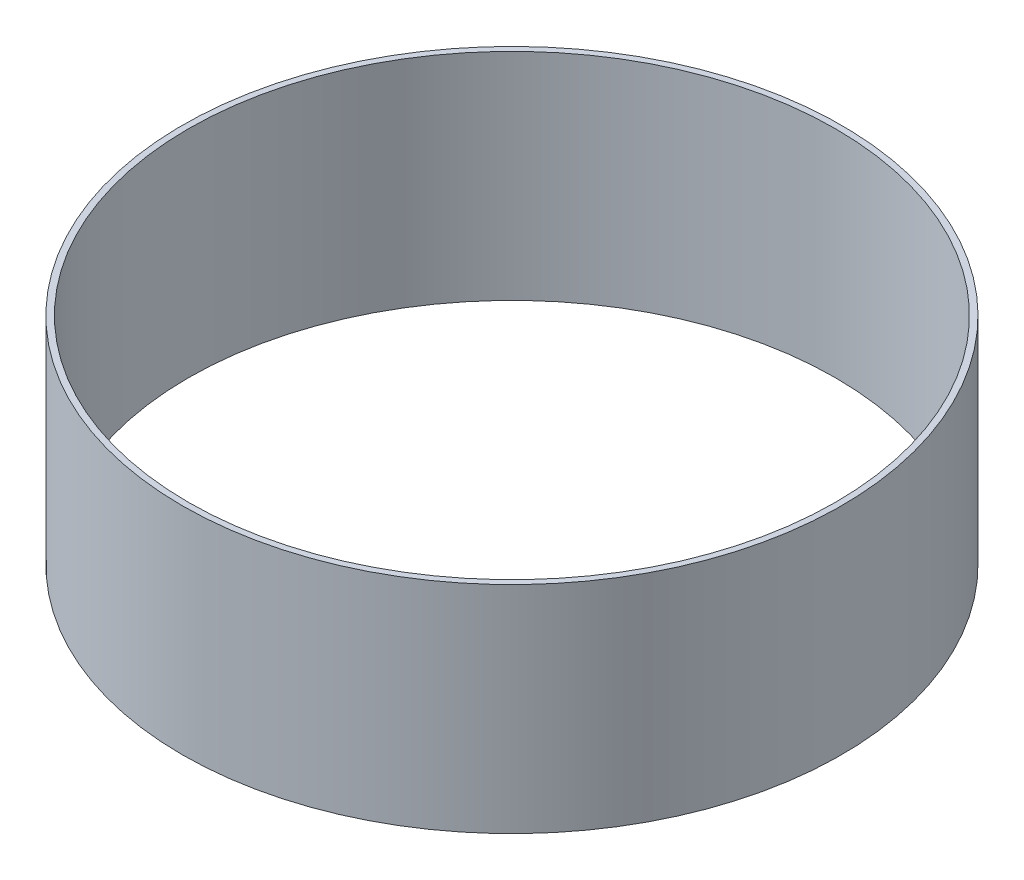
SolidWorks part; units mm, degrees
material "Thornel Mat VMA"
ref_plane "Front Plane" through (0, 0, 0) normal (0, 0, 1) x (1, 0, 0)
ref_plane "Top Plane" through (0, 0, 0) normal (0, 1, 0) x (1, 0, 0)
ref_plane "Right Plane" through (0, 0, 0) normal (1, 0, 0) x (0, 0, -1)
sketch "Sketch1" plane through (0, 0, 0) normal (0, 1, 0) x (1, 0, 0)
  circle A0 centre (0, 0) radius 76.2
  circle A1 centre (0, 0) radius 77.6224
  dimension "D1" = 152.4
  dimension "D2" = 155.2448
extrude "Boss-Extrude1" add sketch "Sketch1" along normal mid plane 50.8
extrude "Cut-Extrude1" [suppressed] cut sketch "Sketch2" against normal blind 5.08
sketch "Sketch2" plane through (54.8873, 0, -54.8873) normal (0.7071, 0, -0.7071) x (0, -1, 0)
  circle A0 centre (0, 0) radius 6.35
pattern_circular "CirPattern1" [suppressed] count 4 over 360
equation "\"airframeInnerDiameter\"= 6in"
equation "\"outerDiameter\"= 6.112in"
equation "\"airframeBulkheadThickness\"= 0.125in"
equation "\"payloadAirframeLength\"= 10in"
equation "\"payloadInnerDiameter\"= 6in - 0.056in"
equation "\"payloadOuterDiameter\"= \"airframeInnerDiameter\""
equation "\"payloadLength\"= 11in"
equation "\"payloadBand\"= 2in"
equation "\"payloadOffsetFromAft\"= 6in"
equation "\"upperAirframeLength\"= 25in"
equation "\"recoveryBayInnerDiameter\"= 5.888in"
equation "\"recoveryLength\"= 8in"
equation "\"recoveryBand\"= 2in"
equation "\"recoveryCouplerOuter\"=\"airframeInnerDiameter\""
equation "\"recoveryOffsetFromAft\"= 3in"
equation "\"midAirframeLength\"= 20in"
equation "\"atsLength\"= 11in"
equation "\"atsInner\"= 5.888in"
equation "\"atsBand\"= 2in"
equation "\"atsCouplerOuter\"=\"airframeInnerDiameter\""
equation "\"atsOffsetFromAft\"= 3in"
equation "\"lowerAirframeLength\"= 40in"
equation "\"motorTubeOuterDiameter\"= 4.25in"
equation "\"motorTubeInnerDiameter\"= 4in"
equation "\"motorTubeLength\"= 32in"
equation "\"centeringRingOuterDiameter\"= \"airframeInnerDiameter\""
equation "\"centeringRingInnerDiameter\"= \"motorTubeOuterDiameter\""
equation "\"centeringRingThickness\"= 0.375in"
equation "\"topCenteringRingOffsetFromAft\"= 16.7in"
equation "\"bottomCenteringRingOffsetFromAft\"= 0.3in"
equation "\"finSlotLength\"= 8in"
equation "\"finSlotOffsetFromAft\"= 3in"
equation "\"finSlotWidth\"= 0.187in"
equation "\"motorCasingOuterDiameter\"= 3in"
equation "\"motorCasingCenteringRingThickness\"= 0.25in"
equation "\"D1@Sketch1\"=\"recoveryCouplerOuter\""
equation "\"D2@Sketch1\"=\"outerDiameter\""
equation "\"D1@Boss-Extrude1\"=\"recoveryBand\""
